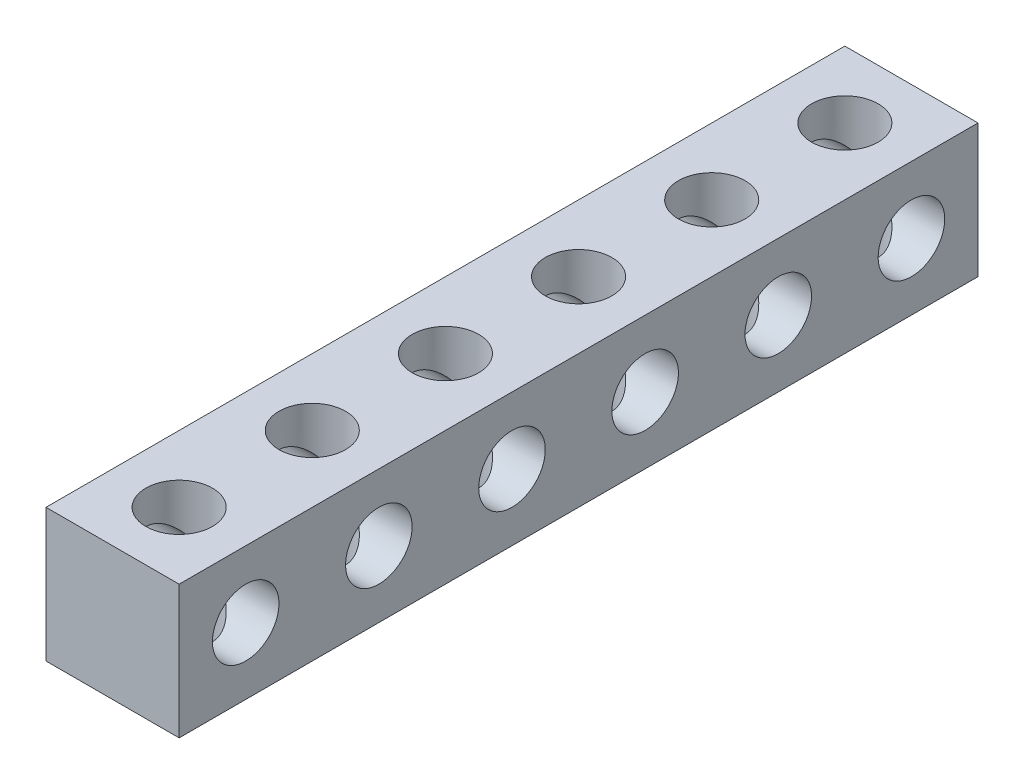
SolidWorks part; units mm, degrees
ref_plane "Front Plane" through (0, 0, 0) normal (0, 0, 1) x (1, 0, 0)
ref_plane "Top Plane" through (0, 0, 0) normal (0, 1, 0) x (1, 0, 0)
ref_plane "Right Plane" through (0, 0, 0) normal (1, 0, 0) x (0, 0, -1)
sketch "Sketch1" plane through (0, 0, 0) normal (0, 0, 1) x (1, 0, 0)
  line L1 (-6.35, -6.35) -> (6.35, -6.35)
  line L2 (-6.35, -6.35) -> (-6.35, 6.35)
  line L3 (-6.35, 6.35) -> (6.35, 6.35)
  line L4 (6.35, -6.35) -> (6.35, 6.35)
  line L5 (-6.35, -6.35) -> (6.35, 6.35) construction
  line L6 (-6.35, 6.35) -> (6.35, -6.35) construction
  point P0 (0, 0)
  dimension "D1" = 12.7
  dimension "D2" = 12.7
extrude "Boss-Extrude1" add sketch "Sketch1" along normal mid plane 76.2
sketch "Sketch2" plane through (0, 6.35, 0) normal (0, 1, 0) x (1, 0, 0)
  line L0 (6.35, 38.1) -> (-6.35, 38.1) construction
  circle A0 centre (0, 31.75) radius 3.175
  circle A1 centre (0, 19.05) radius 3.175
  circle A2 centre (0, 6.35) radius 3.175
  circle A3 centre (0, -6.35) radius 3.175
  circle A4 centre (0, -19.05) radius 3.175
  circle A5 centre (0, -31.75) radius 3.175
  dimension "D1" = 6.35
  dimension "D2" = 6.35
  dimension "D3" = 6
extrude "Cut-Extrude1" cut sketch "Sketch2" against normal through all
sketch "Sketch4" plane through (-6.35, 0, 0) normal (-1, 0, 0) x (0, 0, 1)
  line L0 (38.1, -6.35) -> (38.1, 6.35) construction
  circle A0 centre (31.75, 0) radius 3.175
  circle A1 centre (19.05, 0) radius 3.175
  circle A2 centre (6.35, 0) radius 3.175
  circle A3 centre (-6.35, 0) radius 3.175
  circle A4 centre (-19.05, 0) radius 3.175
  circle A5 centre (-31.75, 0) radius 3.175
  dimension "D1" = 6.35
  dimension "D2" = 6.35
  dimension "D3" = 6
extrude "Cut-Extrude2" cut sketch "Sketch4" against normal through all
